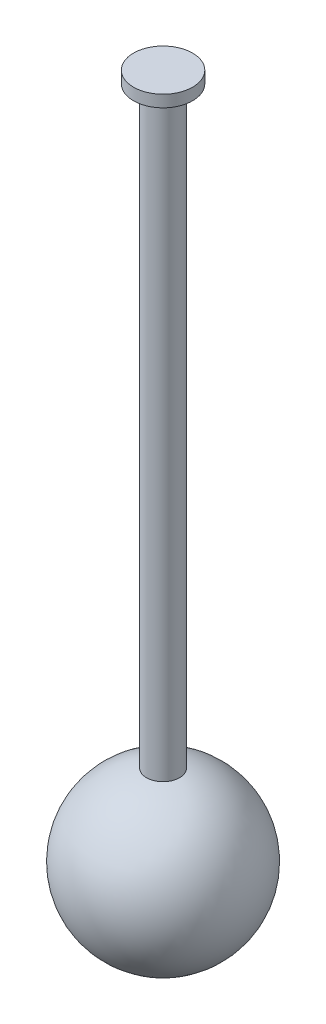
SolidWorks part; units mm, degrees
ref_plane "Ön Düzlem" through (0, 0, 0) normal (0, 0, 1) x (1, 0, 0)
ref_plane "Üst Düzlem" through (0, 0, 0) normal (0, 1, 0) x (1, 0, 0)
ref_plane "Sağ Düzlem" through (0, 0, 0) normal (1, 0, 0) x (0, 0, -1)
sketch "Sketch1" plane through (0, 0, 0) normal (0, 0, 1) x (1, 0, 0)
  line L0 (0, 3.46) -> (0, -3.46) construction
  arc A1 (0, -3.46) -> (0, 3.46) centre (0, 0) ccw
  dimension "D1" = 3.46
revolve "Revolve-Thin1" add sketch "Sketch1" angle 360 about L0
sketch "Sketch3" plane through (0, 0, 0) normal (0, 1, 0) x (1, 0, 0)
  circle A0 centre (0, 0) radius 0.7
  dimension "D1" = 1.4
extrude "Boss-Extrude1" add sketch "Sketch3" along normal blind 28.5
sketch "Sketch4" plane through (0, 28.5, 0) normal (0, 1, 0) x (1, 0, 0)
  circle A0 centre (0, 0) radius 1.25
  dimension "D1" = 2.5
extrude "Boss-Extrude3" add sketch "Sketch4" along normal blind 0.5
